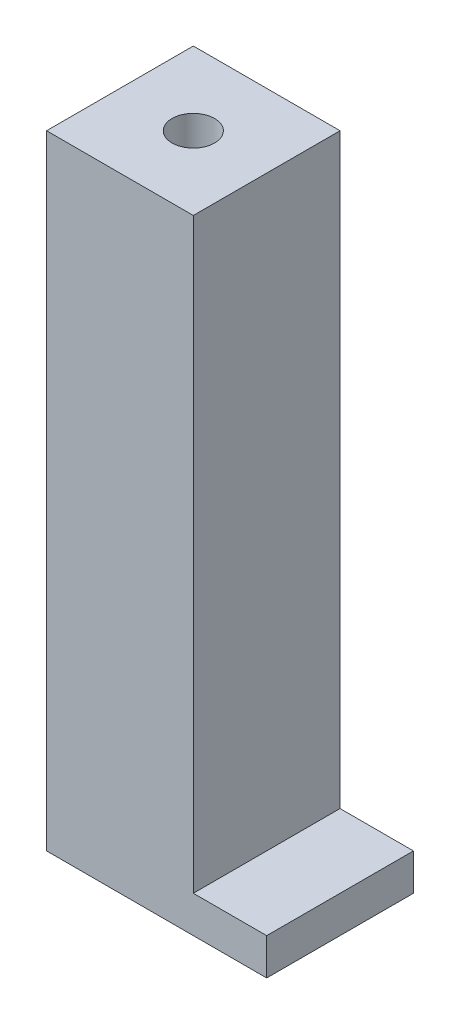
SolidWorks part; units mm, degrees
ref_plane "前视基准面" through (0, 0, 0) normal (0, 0, 1) x (1, 0, 0)
ref_plane "上视基准面" through (0, 0, 0) normal (0, 1, 0) x (1, 0, 0)
ref_plane "右视基准面" through (0, 0, 0) normal (1, 0, 0) x (0, 0, -1)
sketch "草图1" plane through (0, 0, 0) normal (0, 1, 0) x (1, 0, 0)
  line L1 (-10, 10) -> (10, 10)
  line L2 (-10, 10) -> (-10, -10)
  line L3 (-10, -10) -> (10, -10)
  line L4 (10, 10) -> (10, -10)
  line L5 (-10, 10) -> (10, -10) construction
  line L6 (-10, -10) -> (10, 10) construction
  point P0 (0, 0)
  dimension "D1" = 20
  dimension "D2" = 20
extrude "凸台-拉伸1" add sketch "草图1" along normal blind 80
sketch "草图3" plane through (0, 0, 0) normal (0, -1, 0) x (-1, 0, 0)
  line L1 (10, -10) -> (-20, -10)
  line L2 (10, -10) -> (10, 10)
  line L3 (10, 10) -> (-20, 10)
  line L4 (-20, -10) -> (-20, 10)
  dimension "D1" = 30
  dimension "D2" = 20
extrude "凸台-拉伸2" add sketch "草图3" along normal blind 5
sketch "草图4" plane through (0, 80, 0) normal (0, 1, 0) x (1, 0, 0)
  circle A0 centre (0, 0) radius 2.9
  dimension "D1" = 5.8
extrude "切除-拉伸1" cut sketch "草图4" against normal blind 10 contours A0
